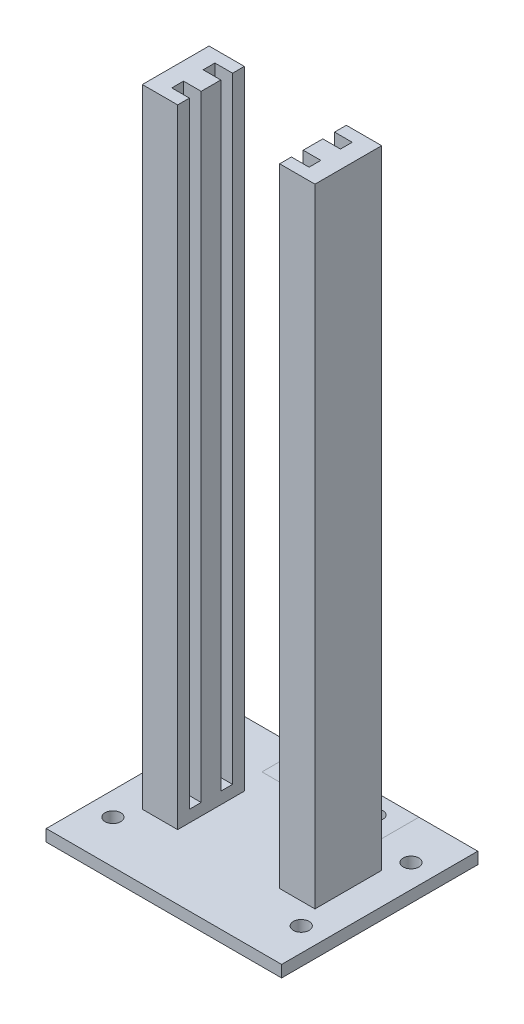
SolidWorks part; units mm, degrees
ref_plane "Front Plane" through (0, 0, 0) normal (0, 0, 1) x (1, 0, 0)
ref_plane "Top Plane" through (0, 0, 0) normal (0, 1, 0) x (1, 0, 0)
ref_plane "Right Plane" through (0, 0, 0) normal (1, 0, 0) x (0, 0, -1)
sketch "Sketch1" plane through (0, 0, 0) normal (0, 1, 0) x (1, 0, 0)
  line L1 (30, 25) -> (-30, 25)
  line L2 (30, 25) -> (30, -25)
  line L3 (30, -25) -> (-30, -25)
  line L4 (-30, 25) -> (-30, -25)
  line L5 (30, 25) -> (-30, -25) construction
  line L6 (30, -25) -> (-30, 25) construction
  point P0 (0, 0)
  dimension "D1" = 50
  dimension "D2" = 60
extrude "Boss-Extrude1" add sketch "Sketch1" along normal blind 3
sketch "Sketch2" plane through (0, 3, 0) normal (0, 1, 0) x (1, 0, 0)
  line L0 (0, 0) -> (-30, 0) construction
  line L1 (-30, 25) -> (-30, -25) construction
  line L2 (0, 0) -> (0, 25) construction
  line L3 (30, 25) -> (-30, 25) construction
  line L4 (13, -8.5) -> (22, -8.5)
  line L5 (-13, 8.5) -> (-22, 8.5)
  line L6 (-13, 8.5) -> (-13, -8.5)
  line L7 (-13, -8.5) -> (-22, -8.5)
  line L8 (-22, 8.5) -> (-22, -8.5)
  line L9 (-13, 8.5) -> (-22, -8.5) construction
  line L10 (-13, -8.5) -> (-22, 8.5) construction
  line L11 (22, 8.5) -> (22, -8.5)
  line L12 (13, 8.5) -> (22, 8.5)
  line L13 (13, 8.5) -> (13, -8.5)
  point P5 (-17.5, 0)
  dimension "D1" = 9
  dimension "D2" = 17
  dimension "D3" = 13
extrude "Boss-Extrude2" add sketch "Sketch2" along normal blind 160
sketch "Sketch3" plane through (0, 163, 0) normal (0, 1, 0) x (1, 0, 0)
  line L0 (-13, -8.5) -> (-13, 8.5) construction
  line L1 (-13, 5.5) -> (-17.5, 5.5)
  line L2 (-13, 5.5) -> (-13, 2.5)
  line L3 (-13, 2.5) -> (-17.5, 2.5)
  line L4 (-17.5, 5.5) -> (-17.5, 2.5)
  line L5 (-13, -8.5) -> (-13, 8.5) construction
  line L6 (-13, -2.5) -> (-17.5, -2.5)
  line L7 (-13, -2.5) -> (-13, -5.5)
  line L8 (-13, -5.5) -> (-17.5, -5.5)
  line L9 (-17.5, -2.5) -> (-17.5, -5.5)
  line L10 (0, 0) -> (0, 9.8393) construction
  line L11 (13, -5.5) -> (17.5, -5.5)
  line L12 (17.5, -2.5) -> (17.5, -5.5)
  line L13 (13, -2.5) -> (17.5, -2.5)
  line L14 (13, -2.5) -> (13, -5.5)
  line L15 (13, 2.5) -> (17.5, 2.5)
  line L16 (17.5, 5.5) -> (17.5, 2.5)
  line L17 (13, 5.5) -> (17.5, 5.5)
  line L18 (13, 5.5) -> (13, 2.5)
  line L19 (-13, 8.5) -> (-22, 8.5) construction
  line L21 (-22, -8.5) -> (-13, -8.5) construction
  dimension "D1" = 4.5
  dimension "D2" = 4.5
  dimension "D3" = 3
  dimension "D4" = 3
  dimension "D5" = 5
  dimension "D6" = 3
  dimension "D7" = 3
extrude "Cut-Extrude1" cut sketch "Sketch3" against normal blind 157
sketch "Sketch4" plane through (-13, 0, 0) normal (1, 0, 0) x (0, 0, -1)
  line L0 (-25, 3) -> (25, 3) construction
  line L1 (-8.5, 163) -> (8.5, 163) construction
  circle A0 centre (0, 7) radius 1.45
  circle A1 centre (0, 160) radius 1.45
  point P4 (0, 0)
  dimension "D1" = 4
  dimension "D2" = 3
extrude "Cut-Extrude2" cut sketch "Sketch4" along normal blind 5 from surface at 26 starting at face at (13, 84, 0)
sketch "Sketch5" plane through (0, 3, 0) normal (0, 1, 0) x (1, 0, 0)
  line L0 (-30, 25) -> (-30, -25) construction
  line L2 (-30, -25) -> (30, -25) construction
  line L3 (30, 25) -> (-30, 25) construction
  line L4 (0, 25) -> (0, -25) construction
  line L5 (30, 0) -> (-30, 0) construction
  line L6 (30, -25) -> (30, 25) construction
  circle A2 centre (-24, 14) radius 2
  circle A3 centre (-24, -14) radius 2
  circle A4 centre (24, -14) radius 2
  circle A5 centre (24, 14) radius 2
  point P18 (0, 0)
  dimension "D4" = 14
  dimension "D5" = 6
extrude "Cut-Extrude3" cut sketch "Sketch5" against normal up to next
sketch "Sketch8" plane through (0, 3, 0) normal (0, 1, 0) x (1, 0, 0)
  line L0 (30, 25) -> (-30, 25) construction
  line L1 (-15, 25) -> (15, 25)
  line L2 (-15, 25) -> (-15, 15)
  line L3 (-15, 15) -> (15, 15)
  line L4 (15, 25) -> (15, 15)
  line L5 (-30, 25) -> (-30, -25) construction
  dimension "D1" = 30
  dimension "D2" = 15
  dimension "D3" = 10
extrude "Boss-Extrude3" add sketch "Sketch8" along normal blind 0.0001
sketch "Sketch9" plane through (0, 3.0001, 0) normal (0, 1, 0) x (1, 0, 0)
  line L0 (-9, 20) -> (9, 20) construction
  line L1 (15, 25) -> (-15, 25) construction
  line L2 (-15, 25) -> (-15, 15) construction
  circle A0 centre (-9, 20) radius 1.8634
  circle A1 centre (9, 20) radius 1.8634
  dimension "D1" = 18
  dimension "D2" = 5
  dimension "D3" = 6
extrude "Cut-Extrude4" cut sketch "Sketch9" against normal up to next
